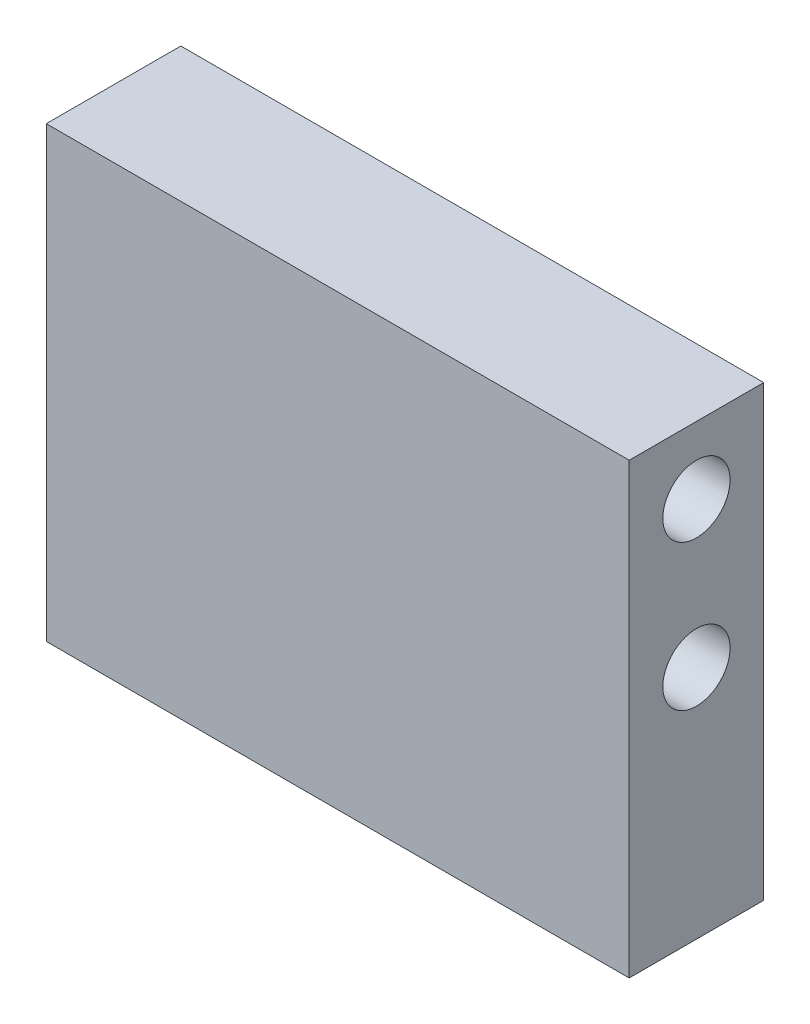
SolidWorks part; units mm, degrees
ref_plane "前视基准面" through (0, 0, 0) normal (0, 0, 1) x (1, 0, 0)
ref_plane "上视基准面" through (0, 0, 0) normal (0, 1, 0) x (1, 0, 0)
ref_plane "右视基准面" through (0, 0, 0) normal (1, 0, 0) x (0, 0, -1)
sketch "草图1" plane through (0, 0, 0) normal (0, 0, 1) x (1, 0, 0)
  line L1 (26, -20) -> (-26, -20)
  line L2 (26, -20) -> (26, 20)
  line L3 (26, 20) -> (-26, 20)
  line L4 (-26, -20) -> (-26, 20)
  line L5 (26, -20) -> (-26, 20) construction
  line L6 (26, 20) -> (-26, -20) construction
  point P0 (0, 0)
  dimension "D1" = 52
  dimension "D2" = 40
extrude "凸台-拉伸1" add sketch "草图1" along normal blind 12
sketch "草图2" plane through (-26, 0, 0) normal (-1, 0, 0) x (0, 0, 1)
  line L0 (12, 20) -> (0, 20) construction
  circle A0 centre (6, 14) radius 3
  circle A3 centre (6, 1) radius 3
  dimension "D1" = 6
  dimension "D3" = 6
  dimension "D4" = 13
  dimension "D2" = 6
extrude "切除-拉伸1" cut sketch "草图2" against normal blind 100
